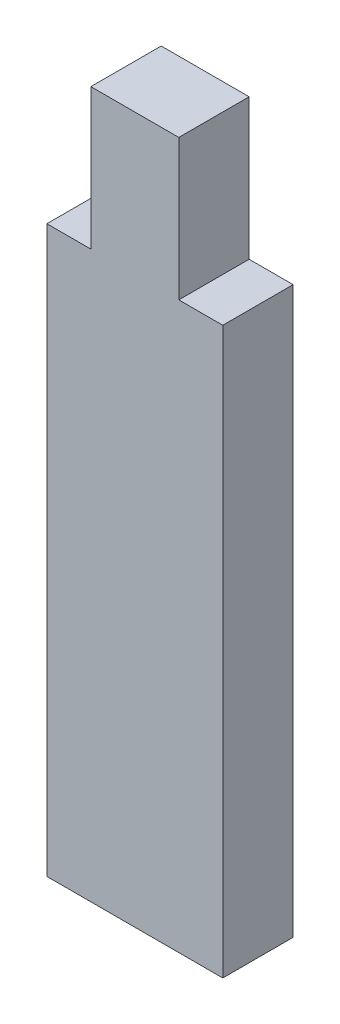
SolidWorks part; units mm, degrees
ref_plane "Front Plane" through (0, 0, 0) normal (0, 0, 1) x (1, 0, 0)
ref_plane "Top Plane" through (0, 0, 0) normal (0, 1, 0) x (1, 0, 0)
ref_plane "Right Plane" through (0, 0, 0) normal (1, 0, 0) x (0, 0, -1)
sketch "Sketch1" plane through (0, 0, 0) normal (0, 0, 1) x (1, 0, 0)
  line L0 (0, 0) -> (0, 32.14)
  line L1 (0, 32.14) -> (2.5, 32.14)
  line L2 (2.5, 32.14) -> (2.5, 40.14)
  line L3 (2.5, 40.14) -> (7.5, 40.14)
  line L4 (7.5, 40.14) -> (7.5, 32.14)
  line L5 (7.5, 32.14) -> (10, 32.14)
  line L6 (10, 32.14) -> (10, 0)
  line L7 (10, 0) -> (0, 0)
  dimension "D1" = 8
  dimension "D2" = 32.14
  dimension "D3" = 5
  dimension "D4" = 10
extrude "Boss-Extrude1" add sketch "Sketch1" along normal blind 4
